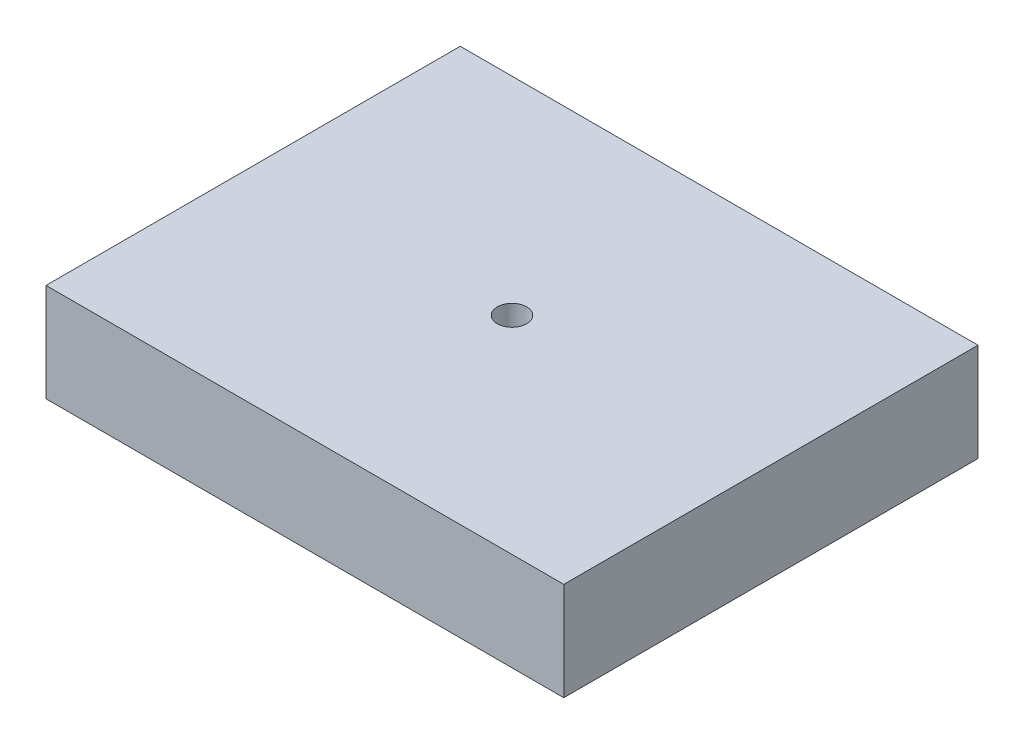
SolidWorks part; units mm, degrees
ref_plane "Front Plane" through (0, 0, 0) normal (0, 0, 1) x (1, 0, 0)
ref_plane "Top Plane" through (0, 0, 0) normal (0, 1, 0) x (1, 0, 0)
ref_plane "Right Plane" through (0, 0, 0) normal (1, 0, 0) x (0, 0, -1)
sketch "Sketch1" plane through (0, 0, 0) normal (0, 1, 0) x (1, 0, 0)
  line L1 (-33.4831, -26.7865) -> (33.4831, -26.7865)
  line L2 (-33.4831, -26.7865) -> (-33.4831, 26.7865)
  line L3 (-33.4831, 26.7865) -> (33.4831, 26.7865)
  line L4 (33.4831, -26.7865) -> (33.4831, 26.7865)
  line L5 (-33.4831, -26.7865) -> (33.4831, 26.7865) construction
  line L6 (-33.4831, 26.7865) -> (33.4831, -26.7865) construction
  point P0 (0, 0)
extrude "Boss-Extrude1" add sketch "Sketch1" along normal blind 12.7
hole_wizard "#6 Clearance Hole1" positions "Sketch2" profile "Sketch3" hole size "#6" standard "ANSI Inch" end condition through all
sketch "Sketch2" plane through (0, 12.7, 0) normal (0, 1, 0) x (1, 0, 0)
  point P0 (0, 0)
sketch "Sketch3" plane through (0, 12.7, 0) normal (1, 0, 0) x (0, 0, 1)
  line L0 (0, 0) -> (0, 12.7)
  line L1 (0, 12.7) -> (1.8986, 12.7)
  line L2 (1.8986, 12.7) -> (1.8986, 0)
  line L5 (1.8986, 0) -> (0, 0)
  line L11 (0, -6.35) -> (0, 107.95) construction
  dimension "Thru Hole Dia." = 3.7973
  dimension "Thru Hole Depth" = 12.7
